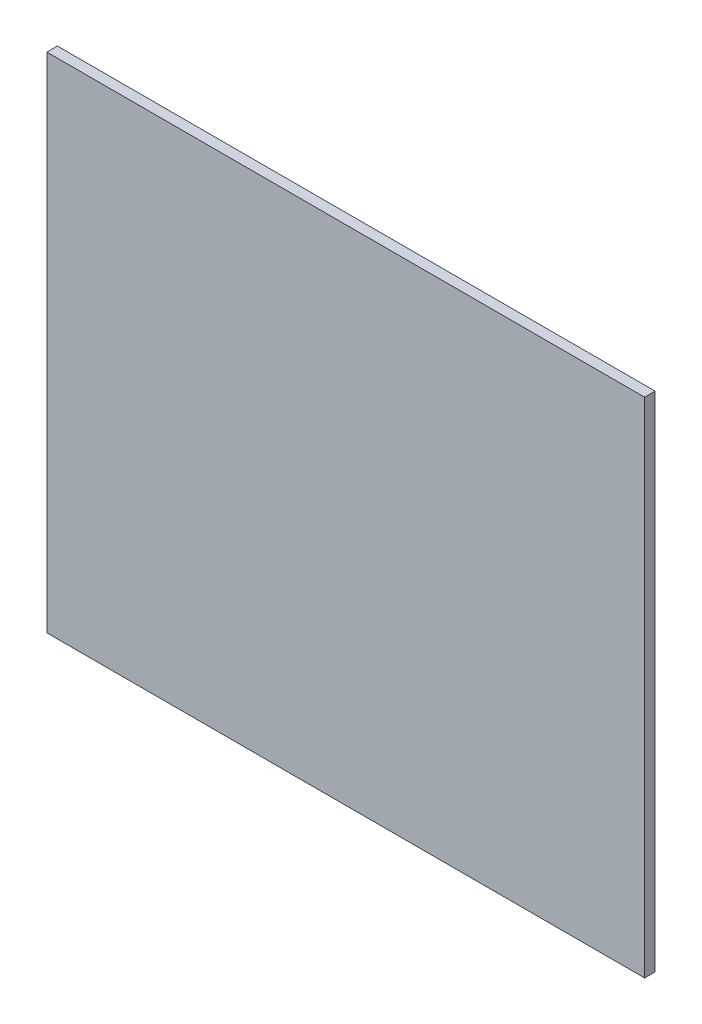
SolidWorks part; units mm, degrees
ref_plane "前视基准面" through (0, 0, 0) normal (0, 0, 1) x (1, 0, 0)
ref_plane "上视基准面" through (0, 0, 0) normal (0, 1, 0) x (1, 0, 0)
ref_plane "右视基准面" through (0, 0, 0) normal (1, 0, 0) x (0, 0, -1)
other "Configuration Table"
sketch "草图1" plane through (0, 0, 0) normal (0, 0, 1) x (1, 0, 0)
  line L1 (241.8943, -231.7467) -> (-326.7674, -231.7467)
  line L2 (241.8943, -231.7467) -> (241.8943, 246.696)
  line L3 (241.8943, 246.696) -> (-326.7674, 246.696)
  line L4 (-326.7674, -231.7467) -> (-326.7674, 246.696)
extrude "凸台-拉伸1" add sketch "草图1" along normal blind 10
